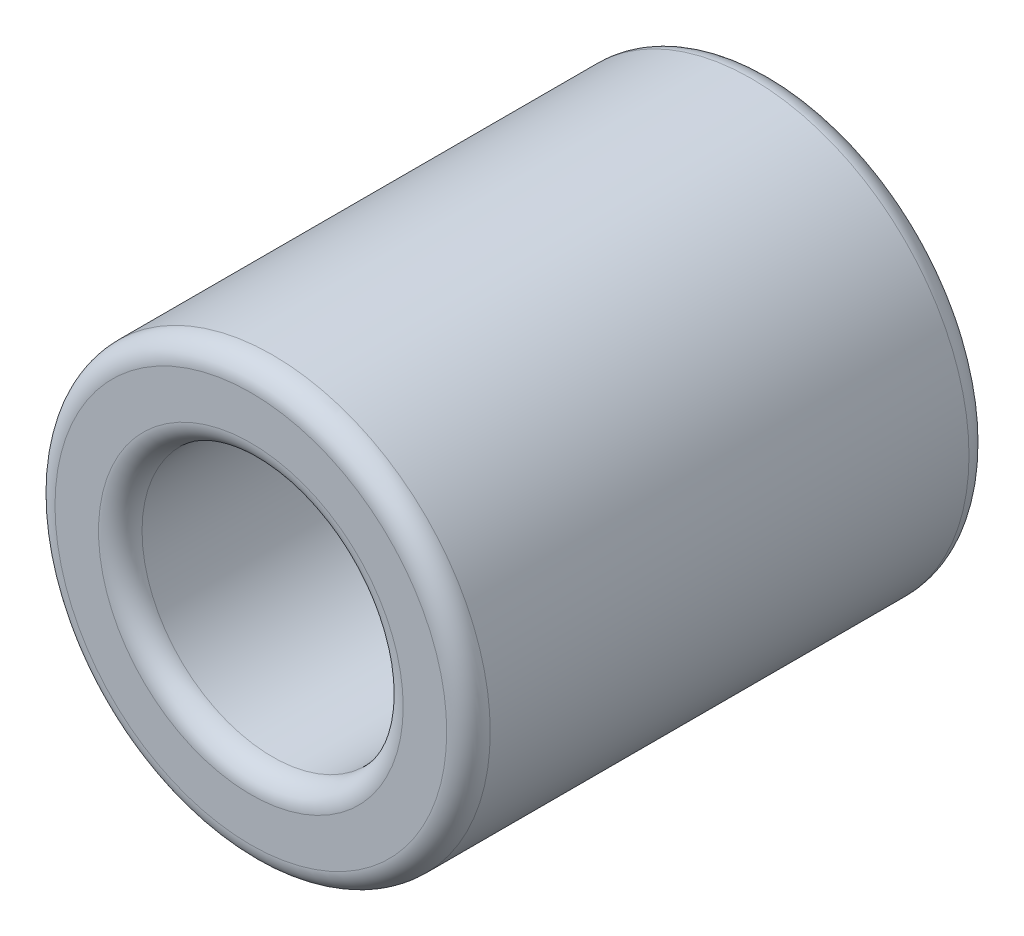
SolidWorks part; units mm, degrees
ref_plane "前视基准面" through (0, 0, 0) normal (0, 0, 1) x (1, 0, 0)
ref_plane "上视基准面" through (0, 0, 0) normal (0, 1, 0) x (1, 0, 0)
ref_plane "右视基准面" through (0, 0, 0) normal (1, 0, 0) x (0, 0, -1)
sketch "草图1" plane through (0, 0, 0) normal (0, 0, 1) x (1, 0, 0)
  circle A0 centre (0, 0) radius 3
  circle A1 centre (0, 0) radius 5
  dimension "D1" = 6
  dimension "D2" = 10
extrude "凸台-拉伸1" add sketch "草图1" along normal blind 12
fillet "圆角1" radius 0.5 4 edges at (3, 0, 0) (5, 0, 0) (3, 0, 12) (5, 0, 12)
